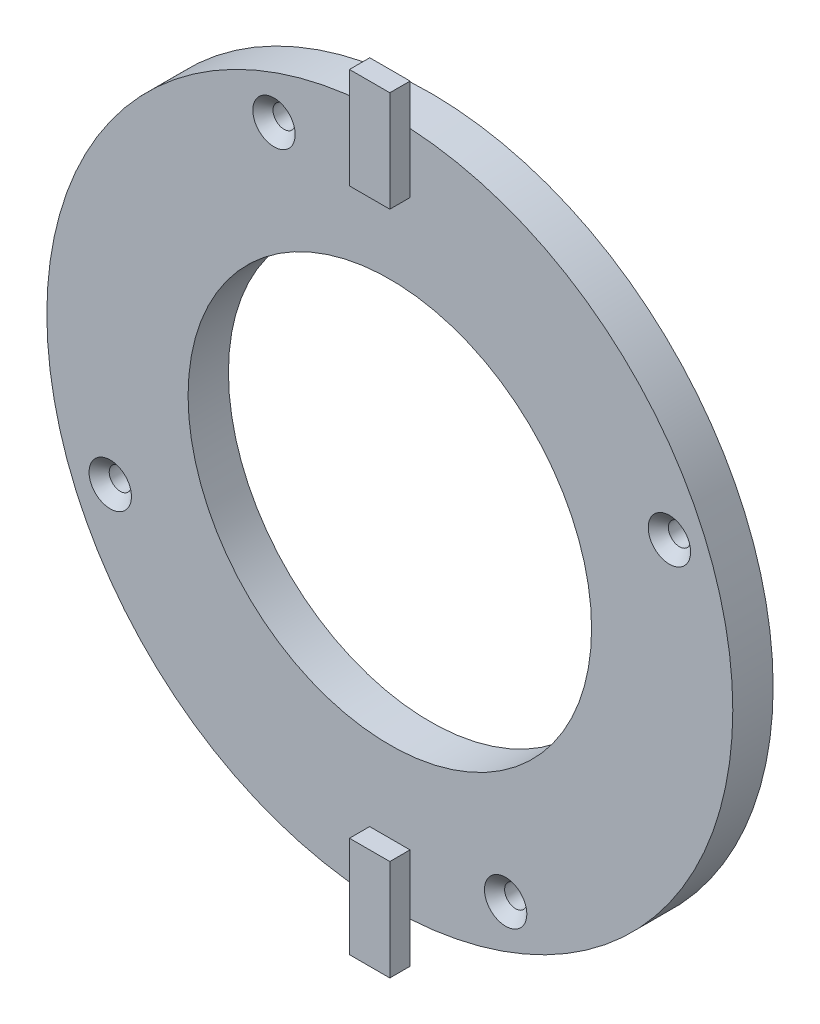
SolidWorks part; units mm, degrees
material "7075-T6 (SN)"
ref_plane "Front Plane" through (0, 0, 0) normal (0, 0, 1) x (1, 0, 0)
ref_plane "Top Plane" through (0, 0, 0) normal (0, 1, 0) x (1, 0, 0)
ref_plane "Right Plane" through (0, 0, 0) normal (1, 0, 0) x (0, 0, -1)
sketch "Sketch1" plane through (0, 0, 0) normal (0, 0, 1) x (1, 0, 0)
  circle A0 centre (0, 0) radius 34
  circle A1 centre (0, 0) radius 20
extrude "Output_Plate" add sketch "Sketch1" along normal blind 4
sketch "Sketch2" plane through (0, 0, 0) normal (0, 0, 1) x (1, 0, 0)
  line L1 (-2, -38) -> (2, -38)
  line L2 (-2, -38) -> (-2, -28)
  line L3 (-2, -28) -> (2, -28)
  line L4 (2, -38) -> (2, -28)
extrude "Y_Tongue_-1" add sketch "Sketch2" along normal blind 2.01 from offset 3.99
sketch "Sketch3" plane through (0, 0, 0) normal (0, 0, 1) x (1, 0, 0)
  line L1 (-2, 28) -> (2, 28)
  line L2 (-2, 28) -> (-2, 38)
  line L3 (-2, 38) -> (2, 38)
  line L4 (2, 28) -> (2, 38)
extrude "Y_Tongue_1" add sketch "Sketch3" along normal blind 2.01 from offset 3.99
sketch "Sketch4" plane through (0, 0, 4) normal (0, 0, 1) x (1, 0, 0)
  circle A0 centre (27.7164, 11.4805) radius 1.1
  circle A1 centre (-11.4805, 27.7164) radius 1.1
  circle A2 centre (-27.7164, -11.4805) radius 1.1
  circle A3 centre (11.4805, -27.7164) radius 1.1
extrude "Four_M2_Clearance" cut sketch "Sketch4" against normal blind 4.01
sketch "Sketch5" plane through (0, 0, 4) normal (0, 0, 1) x (1, 0, 0)
  circle A0 centre (27.7164, 11.4805) radius 2.1
  circle A1 centre (-11.4805, 27.7164) radius 2.1
  circle A2 centre (-27.7164, -11.4805) radius 2.1
  circle A3 centre (11.4805, -27.7164) radius 2.1
extrude "Four_90deg_Countersinks_D4p2" cut sketch "Sketch5" against normal blind 1.1 draft 45
sketch "Sketch6" plane through (0, 0, 0) normal (0, 0, -1) x (-1, 0, 0)
  circle A0 centre (-27.7164, 11.4805) radius 1.51
  circle A1 centre (11.4805, 27.7164) radius 1.51
  circle A2 centre (27.7164, -11.4805) radius 1.51
  circle A3 centre (-11.4805, -27.7164) radius 1.51
extrude "Four_Standoff_Pilot_Pockets_D3p02" cut sketch "Sketch6" against normal blind 1.1
